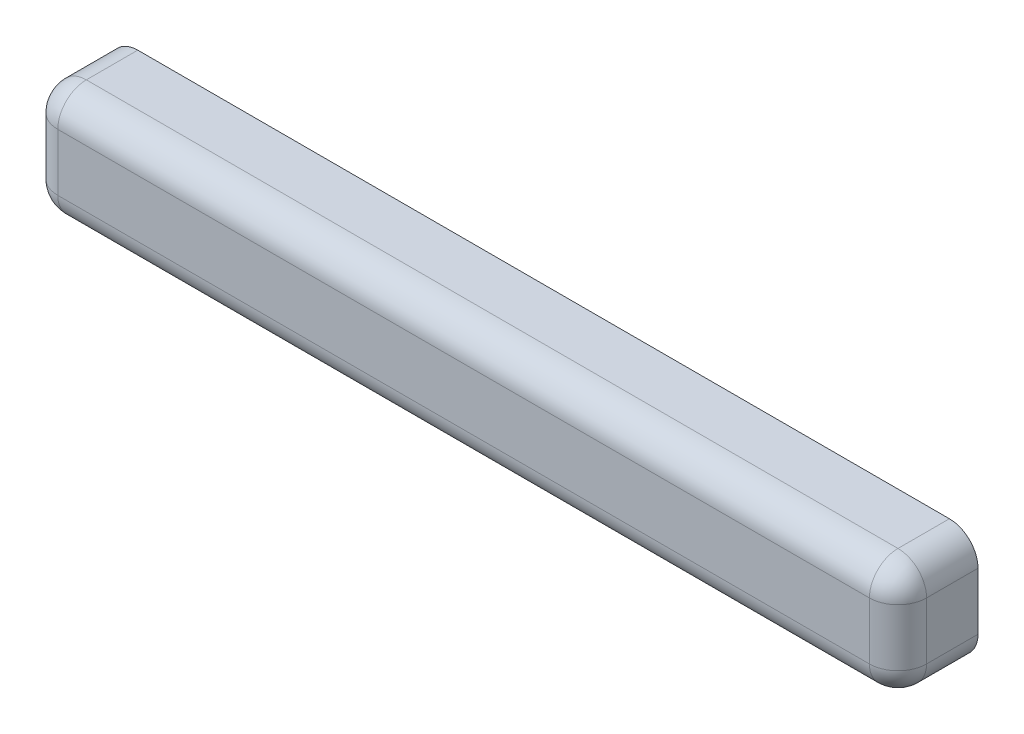
SolidWorks part; units mm, degrees
ref_plane "Front Plane" through (0, 0, 0) normal (0, 0, 1) x (1, 0, 0)
ref_plane "Top Plane" through (0, 0, 0) normal (0, 1, 0) x (1, 0, 0)
ref_plane "Right Plane" through (0, 0, 0) normal (1, 0, 0) x (0, 0, -1)
sketch "Sketch1" plane through (0, 0, 0) normal (0, 0, 1) x (1, 0, 0)
  line L1 (-482.6, 63.5) -> (482.6, 63.5)
  line L2 (-482.6, 63.5) -> (-482.6, -63.5)
  line L3 (-482.6, -63.5) -> (482.6, -63.5)
  line L4 (482.6, 63.5) -> (482.6, -63.5)
  line L5 (-482.6, 63.5) -> (482.6, -63.5) construction
  line L6 (-482.6, -63.5) -> (482.6, 63.5) construction
  point P0 (0, 0)
  dimension "D1" = 127
  dimension "22" = 965.2
extrude "Boss-Extrude1" add sketch "Sketch1" along normal mid plane 88.9
fillet "Fillet1" radius 31.75 2 edges at (0, -63.5, 44.45) (0, 63.5, 44.45)
fillet "Fillet2" radius 31.75 5 edges at (-482.6, -63.5, -15.875) (-482.6, -54.2006, 35.1506) (-482.6, 0, 44.45) (-482.6, 54.2006, 35.1506) (-482.6, 63.5, -15.875)
fillet "Fillet3" radius 31.75 5 edges at (482.6, -63.5, -15.875) (482.6, -54.2006, 35.1506) (482.6, 0, 44.45) (482.6, 54.2006, 35.1506) (482.6, 63.5, -15.875)
sketch "Sketch6" plane through (0, 0, -44.45) normal (0, 0, -1) x (-1, 0, 0)
  line L2 (-11.6556, 0) -> (13.7444, 0) construction
  line L3 (0, -19.5635) -> (0, 19.5635) construction
  circle A0 centre (-11.6556, 0) radius 4.7625
  circle A1 centre (13.7444, 0) radius 4.7625
  circle A2 centre (-271.7163, 0.119) radius 4.7625
  circle A3 centre (-246.3163, 0.119) radius 4.7625
  circle A4 centre (246.3163, 0.119) radius 4.7625
  circle A5 centre (271.7163, 0.119) radius 4.7625
  point P6 (0, 0)
  point P10 (1.0444, 0)
  point P18 (0, 0)
  dimension "D1" = 9.525
  dimension "D2" = 25.4
  dimension "D3" = 25.4
extrude "Cut-Extrude1" cut sketch "Sketch6" against normal blind 25.4
